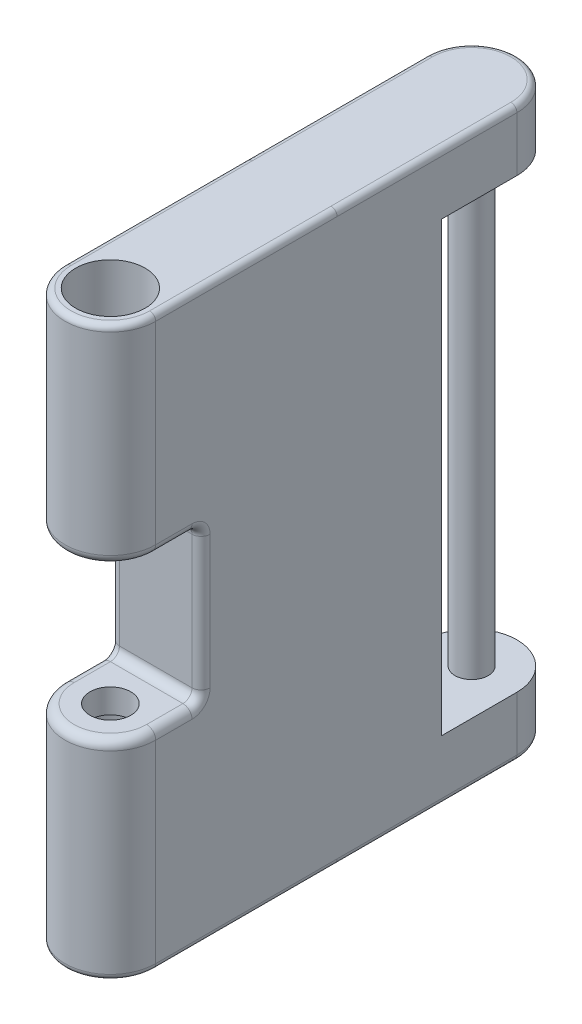
SolidWorks part; units mm, degrees
ref_plane "Front Plane" through (0, 0, 0) normal (0, 0, 1) x (1, 0, 0)
ref_plane "Top Plane" through (0, 0, 0) normal (0, 1, 0) x (1, 0, 0)
ref_plane "Right Plane" through (0, 0, 0) normal (1, 0, 0) x (0, 0, -1)
sketch "Sketch1" plane through (0, 0, 0) normal (0, 1, 0) x (1, 0, 0)
  circle A0 centre (0, 0) radius 1.397
  dimension "D1" = 2.794
extrude "Boss-Extrude1" add sketch "Sketch1" along normal blind 18.796
sketch "Sketch2" plane through (0, 18.796, 0) normal (0, 1, 0) x (1, 0, 0)
  line L0 (-1.397, 0) -> (-1.397, -3.937)
  line L1 (-1.397, -3.937) -> (1.397, -3.937)
  line L2 (1.397, -3.937) -> (1.397, 0)
  line L3 (-3.81, -6.35) -> (3.81, -6.35)
  line L4 (3.81, -6.35) -> (3.81, 0)
  line L5 (-3.81, 0) -> (-3.81, -6.35)
  circle A0 centre (0, 0) radius 1.397 construction
  arc A1 (1.397, 0) -> (-1.397, 0) centre (0, 0) ccw
  arc A2 (3.81, 0) -> (-3.81, 0) centre (0, 0) ccw
  point P7 (0, 0)
  dimension "D1" = 5.334
  dimension "D2" = 1.397
  dimension "D3" = 2.794
  dimension "D4" = 2.413
extrude "Boss-Extrude2" add sketch "Sketch2" along normal blind 5.08 contours L3 L4 A2 L5
sketch "Sketch3" plane through (0, 23.876, 0) normal (0, 1, 0) x (1, 0, 0)
  line L0 (-3.81, -6.35) -> (-3.81, -15.113)
  line L1 (-3.81, -6.35) -> (3.81, -6.35)
  line L5 (-3.81, -15.113) -> (3.81, -15.113)
  line L6 (3.81, -6.35) -> (3.81, -15.113)
  line L8 (-1.397, -6.35) -> (-1.397, -12.7) construction
  line L9 (1.397, -6.35) -> (1.397, -12.7) construction
  line L10 (-1.397, -12.7) -> (1.397, -12.7) construction
  line L11 (-3.81, -3.937) -> (3.81, -3.937) construction
  line L12 (-3.81, -3.937) -> (-3.81, -15.113) construction
  line L13 (3.81, -3.937) -> (3.81, -15.113) construction
  line L14 (-1.397, -6.35) -> (1.397, -6.35) construction
  line L15 (3.81, -6.35) -> (3.81, 0) construction
  line L16 (-3.81, -6.35) -> (3.81, -6.35) construction
  point P11 (0, -15.113)
  dimension "D1" = 8.763
  dimension "D2" = 7.62
  dimension "D3" = 2.413
extrude "Boss-Extrude3" add sketch "Sketch3" against normal blind 23.876 contours L1 L6 L5 L0
mirror "Mirror1" about plane through (0, 0, 0) normal (0, 1, 0) of bodies 103
fillet "Fillet1" radius 0.508 6 edges at (-3.81, -23.876, 7.5565) (3.81, -23.876, 7.5565) (0, -23.876, -3.81) (-3.81, 23.876, 7.5565) (3.81, 23.876, 7.5565) (0, 23.876, -3.81)
sketch "Sketch8" plane through (0, 23.876, 0) normal (0, 1, 0) x (1, 0, 0)
  line L1 (-3.81, -15.113) -> (3.81, -15.113)
  line L2 (-3.81, -15.113) -> (-3.81, -30.353)
  line L4 (3.81, -15.113) -> (3.81, -30.353)
  arc A0 (-3.81, -30.353) -> (3.81, -30.353) centre (0, -30.353) ccw
  dimension "D1" = 19.05
  dimension "D2" = 7.62
extrude "Boss-Extrude5" add sketch "Sketch8" against normal up to surface (47.752 mm away)
fillet "Fillet3" radius 0.508 14 edges at (3.556, -23.876, 15.113) (-3.81, 23.622, 15.113) (-3.81, 23.876, 22.733) (0, 23.876, 34.163) (3.81, 23.876, 22.733) (3.556, 23.876, 15.113) (-3.556, 23.876, 15.113) (0, -23.876, 34.163) (3.81, -23.876, 22.733) (3.81, -23.622, 15.113) (3.81, 23.622, 15.113) (-3.81, -23.622, 15.113) (-3.556, -23.876, 15.113) (-3.81, -23.876, 22.733)
sketch "Sketch9" plane through (-3.81, 0, 0) normal (-1, 0, 0) x (0, 0, 1)
  line L0 (34.163, -23.368) -> (34.163, 23.368) construction
  line L1 (34.163, 6.35) -> (26.543, 6.35)
  line L2 (34.163, 6.35) -> (34.163, -6.35)
  line L3 (34.163, -6.35) -> (26.543, -6.35)
  line L4 (26.543, 6.35) -> (26.543, -6.35)
  point P6 (26.543, 0)
  dimension "D1" = 12.7
  dimension "D2" = 7.62
extrude "Cut-Extrude2" cut sketch "Sketch9" against normal through all both and the other way through all
fillet "Fillet4" radius 0.762 10 edges at (0, 6.35, 34.163) (0, -6.35, 34.163) (-3.81, -6.35, 28.448) (-3.81, 6.35, 28.448) (3.81, 6.35, 28.448) (3.81, -6.35, 28.448) (-3.81, 0, 26.543) (0, 6.35, 26.543) (3.81, 0, 26.543) (0, -6.35, 26.543)
sketch "Sketch10" plane through (0, 23.876, 0) normal (0, 1, 0) x (1, 0, 0)
  circle A0 centre (0, -30.353) radius 2.921
  dimension "D1" = 5.842
extrude "Cut-Extrude3" cut sketch "Sketch10" against normal blind 15.494 and the other way through all
sketch "Sketch11" plane through (0, 8.382, 0) normal (0, 1, 0) x (1, 0, 0)
  circle A0 centre (0, -30.353) radius 1.7145
  dimension "D1" = 3.429
extrude "Cut-Extrude4" cut sketch "Sketch11" against normal through all both and the other way through all
sketch "Sketch12" plane through (0, -23.876, 0) normal (0, -1, 0) x (1, 0, 0)
  circle A0 centre (0, 30.353) radius 3.3655
  dimension "D1" = 6.731
extrude "Cut-Extrude5" cut sketch "Sketch12" against normal blind 15.494 and the other way through all
